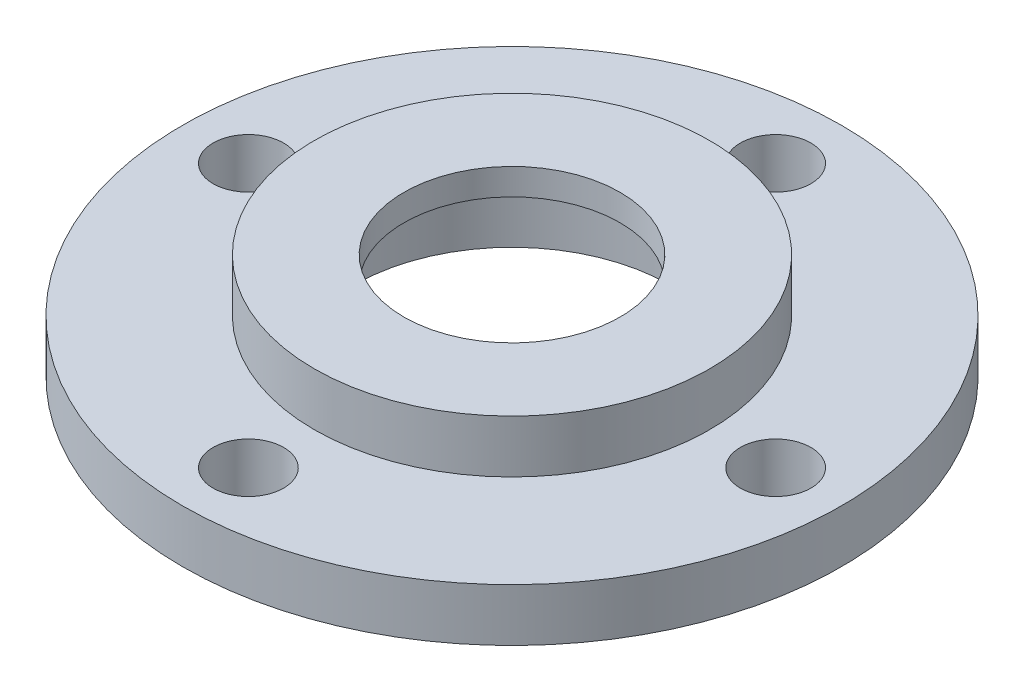
SolidWorks part; units mm, degrees
ref_plane "Front Plane" through (0, 0, 0) normal (0, 0, 1) x (1, 0, 0)
ref_plane "Top Plane" through (0, 0, 0) normal (0, 1, 0) x (1, 0, 0)
ref_plane "Right Plane" through (0, 0, 0) normal (1, 0, 0) x (0, 0, -1)
sketch "Sketch1" plane through (0, 0, 0) normal (0, 1, 0) x (1, 0, 0)
  circle A0 centre (0, 0) radius 15.875
  dimension "D1" = 31.75
extrude "Boss-Extrude1" add sketch "Sketch1" along normal blind 2.54
sketch "Sketch2" plane through (0, 2.54, 0) normal (0, 1, 0) x (1, 0, 0)
  circle A0 centre (0, 0) radius 9.525
  dimension "D1" = 19.05
extrude "Boss-Extrude2" add sketch "Sketch2" along normal blind 2.54
sketch "Sketch3" plane through (0, 0, 0) normal (0, -1, 0) x (1, 0, 0)
  circle A0 centre (0, 0) radius 7.62
  dimension "D1" = 15.24
extrude "Cut-Extrude1" cut sketch "Sketch3" against normal blind 3.81
sketch "Sketch4" plane through (0, 5.08, 0) normal (0, 1, 0) x (1, 0, 0)
  circle A0 centre (0, 0) radius 5.207
  point P2 (0, 0)
  dimension "D1" = 10.414
extrude "Cut-Extrude2" cut sketch "Sketch4" against normal up to next
sketch "Sketch5" plane through (0, 2.54, 0) normal (0, 1, 0) x (1, 0, 0)
  line L0 (0, 15.875) -> (0, 0) construction
  circle A0 centre (0, 12.7) radius 1.7
  circle A1 centre (0, 0) radius 15.875 construction
  circle A2 centre (12.7, 0) radius 1.7
  circle A3 centre (0, -12.7) radius 1.7
  circle A4 centre (-12.7, 0) radius 1.7
  point P8 (0, 0)
  point P10 (0, 0)
  point P11 (0, 0)
  point P18 (0, 0)
  point P19 (0, 0)
  point P20 (-9.9428, 2.1272)
  point P21 (0, 0)
  point P23 (0, 0)
  point P24 (0, 12.3293)
  dimension "D2" = 3.4
  dimension "D1" = 12.7
  dimension "D3" = 4
extrude "Cut-Extrude3" cut sketch "Sketch5" against normal up to next
